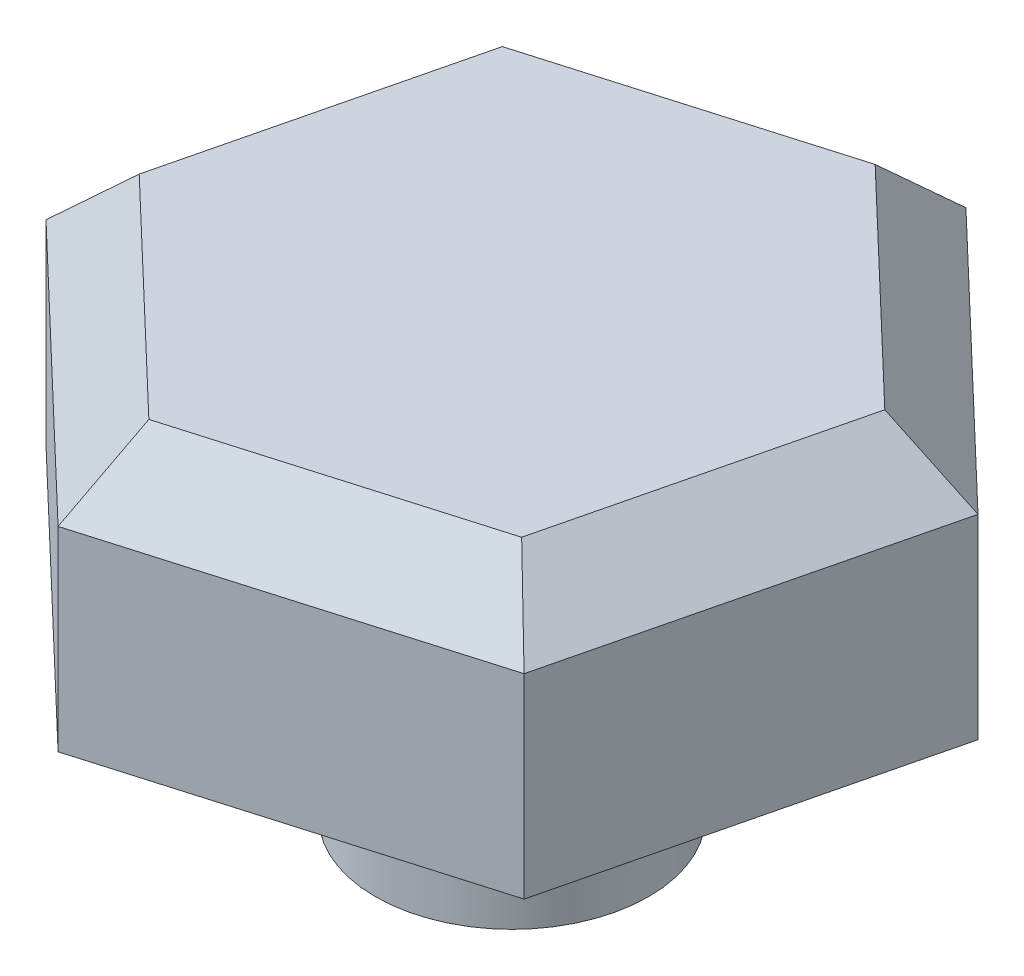
SolidWorks part; units mm, degrees
ref_plane "前视基准面" through (0, 0, 0) normal (0, 0, 1) x (1, 0, 0)
ref_plane "上视基准面" through (0, 0, 0) normal (0, 1, 0) x (1, 0, 0)
ref_plane "右视基准面" through (0, 0, 0) normal (1, 0, 0) x (0, 0, -1)
sketch "草图1" plane through (0, 0, 0) normal (0, 1, 0) x (1, 0, 0)
  line L1 (4.1742, -3.9887) -> (5.5414, 1.6206)
  line L2 (5.5414, 1.6206) -> (1.3672, 5.6093)
  line L3 (1.3672, 5.6093) -> (-4.1742, 3.9887)
  line L4 (-4.1742, 3.9887) -> (-5.5414, -1.6206)
  line L5 (-5.5414, -1.6206) -> (-1.3672, -5.6093)
  line L6 (-1.3672, -5.6093) -> (4.1742, -3.9887)
  circle A0 centre (0, 0) radius 5 construction
  dimension "D1" = 10
extrude "拉伸1" add sketch "草图1" along normal blind 4
chamfer "倒角1" distance 1 angle 45 6 edges at (-3.4543, 4, 3.615) (-4.8578, 4, -1.184) (-1.4035, 4, -4.799) (3.4543, 4, -3.615) (4.8578, 4, 1.184) (1.4035, 4, 4.799)
sketch "草图2" plane through (0, 0, 0) normal (0, -1, 0) x (1, 0, 0)
  circle A0 centre (0, 0) radius 2.1
  dimension "D1" = 4.2
extrude "拉伸2" add sketch "草图2" along normal blind 3
